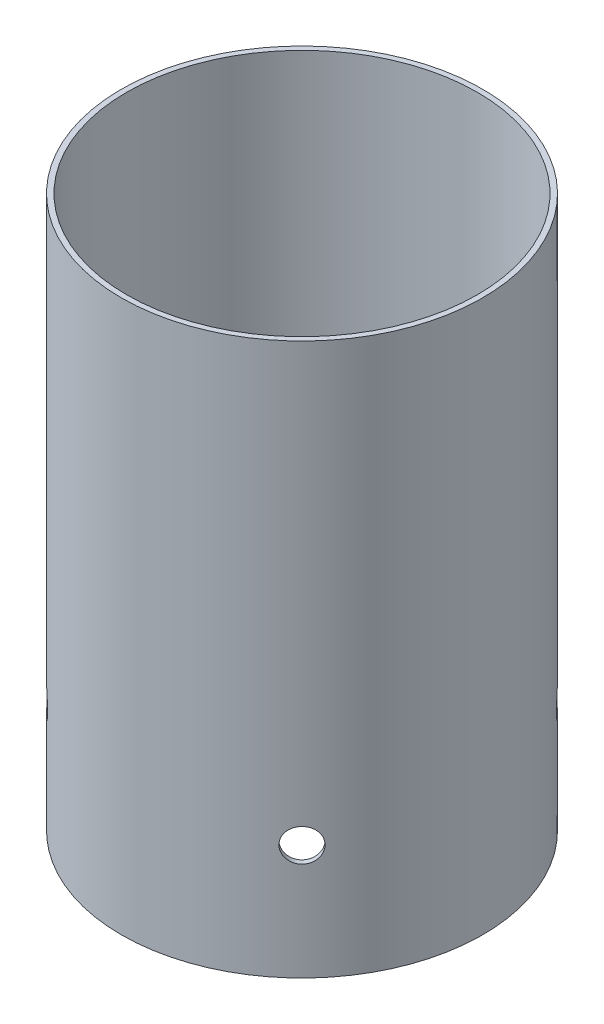
SolidWorks part; units mm, degrees
ref_plane "Front Plane" through (0, 0, 0) normal (0, 0, 1) x (1, 0, 0)
ref_plane "Top Plane" through (0, 0, 0) normal (0, 1, 0) x (1, 0, 0)
ref_plane "Right Plane" through (0, 0, 0) normal (1, 0, 0) x (0, 0, -1)
sketch "Sketch1" plane through (0, 0, 0) normal (0, 1, 0) x (1, 0, 0)
  circle A0 centre (0, 0) radius 38.15
  circle A1 centre (0, 0) radius 39.3
  dimension "D1" = 78.6
  dimension "D2" = 76.3
extrude "Boss-Extrude1" add sketch "Sketch1" along normal blind 120
ref_plane "Plane1" through (-27.7893, 0, -27.7893) normal (-0.7071, 0, -0.7071) x (0, -1, 0)
sketch "Sketch2" plane through (-27.7893, 0, -27.7893) normal (-0.7071, 0, -0.7071) x (0, -1, 0)
  circle A0 centre (-25, 0) radius 3.55
  dimension "D1" = 25
  dimension "D2" = 7.1
extrude "Cut-Extrude1" cut sketch "Sketch2" against normal up to next
pattern_circular "CirPattern1" count 4 over 360 about axis through (0, 120, 0) along (0, -1, 0) of "Cut-Extrude1"
